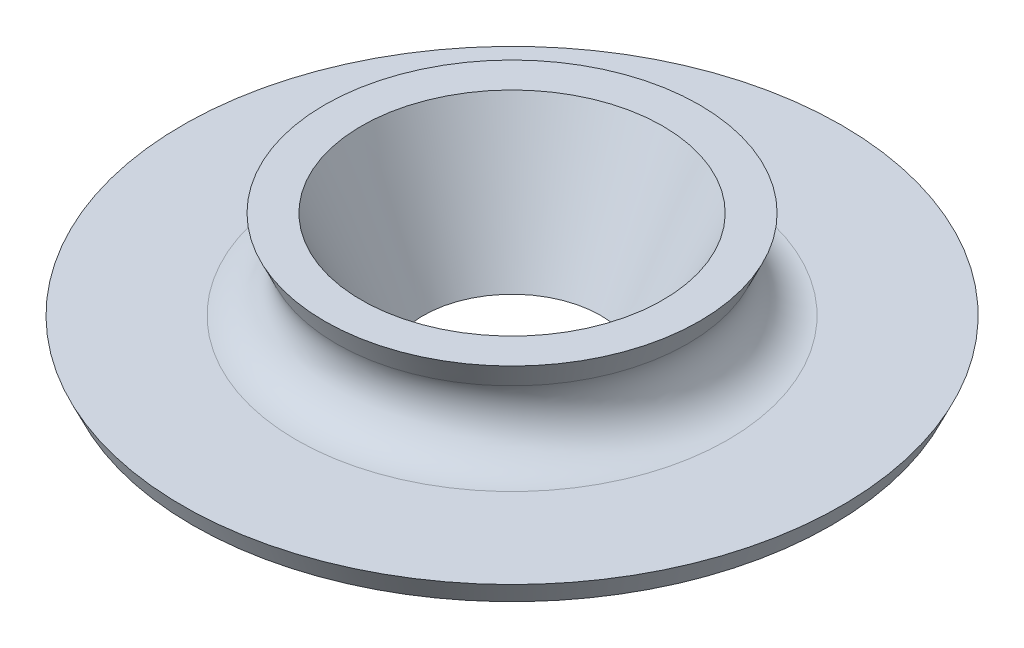
SolidWorks part; units mm, degrees
ref_plane "Front Plane" through (0, 0, 0) normal (0, 0, 1) x (1, 0, 0)
ref_plane "Top Plane" through (0, 0, 0) normal (0, 1, 0) x (1, 0, 0)
ref_plane "Right Plane" through (0, 0, 0) normal (1, 0, 0) x (0, 0, -1)
sketch "Sketch1" plane through (0, 0, 0) normal (0, 0, 1) x (1, 0, 0)
  line L0 (0, 0) -> (0, 32.7815) construction
  line L1 (-25.4, 0.3421) -> (-32.4064, 0.3421)
  line L2 (-32.4064, 0.3421) -> (-35.3675, 6.6921)
  line L3 (-35.3675, 6.6921) -> (-91.4191, 6.6921)
  line L4 (-91.4191, 6.6921) -> (-94.3802, 13.0421)
  line L5 (-94.3802, 13.0421) -> (-41.8318, 13.0421)
  line L6 (-41.8318, 13.0421) -> (-53.676, 38.4421)
  line L7 (-53.676, 38.4421) -> (-43.1663, 38.4421)
  line L8 (-43.1663, 38.4421) -> (-25.4, 0.3421)
  point P5 (-28.9032, 0.3421)
  point P12 (-53.8711, 13.0421)
  point P13 (0, 0)
  point P14 (0, 0)
  point P15 (-92.8996, 9.8671)
  dimension "D1" = 38.1
  dimension "D2" = 6.35
  dimension "D3" = 6.35
  dimension "D4" = 9.525
  dimension "D5" = 6.35
  dimension "D6" = 25.4
  dimension "D7" = 57.15
  dimension "D8" = 25
revolve "Revolve1" add sketch "Sketch1" angle 360 about L0
fillet "Fillet1" radius 12.7 1 edges at (0, 13.0421, -41.8318)
